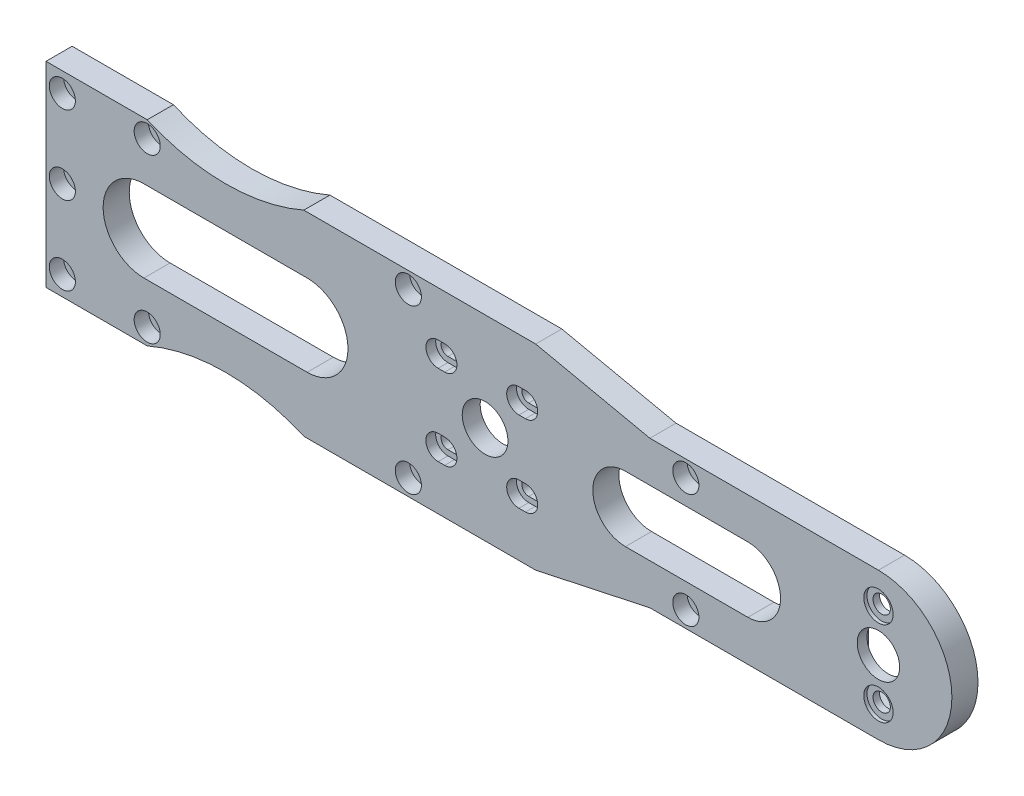
SolidWorks part; units mm, degrees
material "6061 合金"
ref_plane "前视基准面" through (0, 0, 0) normal (0, 0, 1) x (1, 0, 0)
ref_plane "上视基准面" through (0, 0, 0) normal (0, 1, 0) x (1, 0, 0)
ref_plane "右视基准面" through (0, 0, 0) normal (1, 0, 0) x (0, 0, -1)
sketch "草图1" plane through (0, 0, 0) normal (0, 0, 1) x (1, 0, 0)
  line L0 (128.1737, 22.5) -> (58.1737, 22.5)
  line L1 (23.1737, 30) -> (-47.8471, 30)
  line L2 (-96.8263, 0) -> (-46.8263, 0) construction
  line L3 (23.1737, -30) -> (-47.8471, -30)
  line L4 (-126.8263, 30) -> (-126.8263, -30)
  line L5 (-95.8054, -30) -> (-126.8263, -30)
  line L6 (-95.8054, 30) -> (-126.8263, 30)
  line L7 (58.1737, 22.5) -> (23.1737, 30)
  line L8 (-96.8263, 12.5) -> (-46.8263, 12.5)
  line L9 (23.1737, -30) -> (58.1737, -22.5)
  line L10 (58.1737, -22.5) -> (128.1737, -22.5)
  line L11 (-96.8263, -12.5) -> (-46.8263, -12.5)
  arc A0 (128.1737, -22.5) -> (128.1737, 22.5) centre (128.1737, 0) ccw
  arc A1 (-96.8263, 12.5) -> (-96.8263, -12.5) centre (-96.8263, 0) ccw
  arc A2 (-46.8263, -12.5) -> (-46.8263, 12.5) centre (-46.8263, 0) ccw
  arc A3 (-95.8054, 30) -> (-47.8471, 30) centre (-71.8263, 85) ccw
  arc A4 (-47.8471, -30) -> (-95.8054, -30) centre (-71.8263, -85) ccw
  point P15 (-71.8263, 0)
  dimension "D3" = 45
  dimension "D7" = 12.5
  dimension "D11" = 55
  dimension "D12" = 120
  dimension "D13" = 55
  dimension "D1" = 60
  dimension "D2" = 255
  dimension "D4" = 70
  dimension "D5" = 30
  dimension "D6" = 70
  dimension "D8" = 50
  dimension "D9" = 30
  dimension "D10" = 150
extrude "凸台-拉伸1" add sketch "草图1" along normal blind 8
sketch "草图2" plane through (0, 0, 8) normal (0, 0, 1) x (1, 0, 0)
  line L0 (50.6737, 0) -> (88.1737, 0) construction
  line L1 (50.6737, 10) -> (88.1737, 10)
  line L2 (50.6737, -10) -> (88.1737, -10)
  arc A0 (50.6737, 10) -> (50.6737, -10) centre (50.6737, 0) ccw
  arc A1 (88.1737, -10) -> (88.1737, 10) centre (88.1737, 0) ccw
  point P3 (69.4237, 0)
  dimension "D1" = 40
  dimension "D3" = 10
  dimension "D2" = 37.5
extrude "切除-拉伸1" cut sketch "草图2" against normal blind 10
hole_wizard "M4 六角凹头螺钉的柱形沉头孔1" positions "草图4" profile "草图3" counterbore size "M4" standard "Iso" end condition through all
sketch "草图4" plane through (0, 0, 8) normal (0, 0, 1) x (1, 0, 0)
  line L0 (-126.8263, 30) -> (-126.8263, -30) construction
  arc A0 (-96.8263, 12.5) -> (-96.8263, -12.5) centre (-96.8263, 0) ccw construction
  point P0 (-121.8263, 0)
  point P2 (-121.8263, -24)
  point P4 (-121.8263, 24)
  point P6 (-95.8263, 25)
  point P8 (-95.8263, -25)
  point P10 (-15.8263, -25)
  point P12 (-15.8263, 25)
  point P18 (-109.3263, 0)
  point P38 (69.1737, 17.5)
  point P40 (69.1737, -17.5)
  dimension "D1" = 5
  dimension "D2" = 24
  dimension "D3" = 24
  dimension "D4" = 0
  dimension "D5" = 26
  dimension "D6" = 80
  dimension "D7" = 50
  dimension "D8" = 25
  dimension "D9" = 85
  dimension "D10" = 35
  dimension "D11" = 17.5
sketch "草图3" plane through (-121.8263, 0, 8) normal (1, 0, 0) x (0, -1, 0)
  line L0 (0, 0) -> (0, 8)
  line L1 (0, 8) -> (2.25, 8)
  line L3 (2.25, 8) -> (2.25, 4.4)
  line L4 (2.25, 4.4) -> (4, 4.4)
  line L5 (4, 4.4) -> (4, 0)
  line L7 (4, 0) -> (0, 0)
  line L11 (0, -6.35) -> (0, 107.95) construction
  dimension "通孔孔直径" = 4.5
  dimension "通孔孔深度" = 8
  dimension "柱形沉头孔直径" = 8
  dimension "柱形沉头孔深度" = 4.4
sketch "草图11" plane through (0, 0, 0) normal (0, 0, -1) x (-1, 0, 0)
  line L9 (-88.1737, -13) -> (-50.6737, -13)
  line L10 (-50.6737, 13) -> (-88.1737, 13)
  line L11 (96.423, -27) -> (123.8263, -27)
  line L12 (-88.1737, 20.25) -> (-115.4771, 20.25)
  line L14 (123.8263, 27) -> (96.423, 27)
  line L29 (123.8263, -27) -> (123.8263, 27)
  line L30 (47.2295, 27) -> (-22.8559, 27)
  line L31 (-22.8559, 27) -> (-57.8559, 19.5)
  line L32 (-57.8559, 19.5) -> (-128.1737, 19.5)
  line L38 (-128.1737, -19.5) -> (-57.8559, -19.5)
  line L39 (-57.8559, -19.5) -> (-22.8559, -27)
  line L40 (-22.8559, -27) -> (47.2295, -27)
  line L41 (101.8263, -27) -> (101.8263, -25)
  line L42 (114.8263, 27) -> (101.8263, 27)
  line L45 (-115.2449, -19.5) -> (-88.1737, -19.5)
  line L55 (-100.6534, 3.6412) -> (-112.4771, 3.6412)
  line L60 (96.8263, 15.5) -> (46.8263, 15.5)
  line L61 (46.8263, -15.5) -> (96.8263, -15.5)
  line L62 (96.8263, 15.5) -> (46.8263, 15.5)
  line L63 (46.8263, -15.5) -> (96.8263, -15.5)
  line L65 (-88.1737, 13) -> (-88.1737, 20.25)
  line L66 (-88.1737, -13) -> (-88.1737, -19.5)
  line L70 (101.8263, 27) -> (101.8263, 25)
  line L71 (114.8263, 30) -> (114.8263, -30)
  line L72 (114.8263, 27) -> (114.8263, -27)
  line L74 (47.2295, 27) -> (24.8263, 27)
  line L78 (101.8263, -27) -> (114.8263, -27)
  line L80 (24.8263, 27) -> (24.8263, -27)
  line L82 (24.8263, -27) -> (47.2295, -27)
  line L83 (-115.4771, 20.25) -> (-115.4771, 9.9216)
  line L86 (-112.2449, -4.3588) -> (-100.4212, -4.3588)
  line L87 (-115.2449, -10.2748) -> (-115.2449, -19.5)
  arc A3 (47.2295, 27) -> (96.423, 27) centre (71.8263, 85) ccw
  arc A4 (47.2295, 27) -> (89.8377, 24.6296) centre (71.8263, 85) ccw
  arc A5 (96.423, -27) -> (47.2295, -27) centre (71.8263, -85) ccw
  arc A6 (89.8377, -24.6296) -> (47.2295, -27) centre (71.8263, -85) ccw
  arc A9 (-128.1737, 19.5) -> (-128.1737, -19.5) centre (-128.1737, 0) ccw
  arc A16 (-50.6737, -13) -> (-50.6737, 13) centre (-50.6737, 0) ccw
  arc A17 (-88.1737, 13) -> (-88.1737, -13) centre (-88.1737, 0) ccw
  arc A18 (101.8263, -25) -> (89.8377, -24.6296) centre (95.8263, -25) ccw
  arc A19 (-88.1737, 13) -> (-100.6534, 3.6412) centre (-88.1737, 0) ccw
  arc A43 (-112.4771, 3.6412) -> (-115.4771, 9.9216) centre (-128.1737, 0) ccw
  arc A47 (-100.4212, -4.3588) -> (-88.1737, -13) centre (-88.1737, 0) ccw
  arc A49 (96.8263, -15.5) -> (96.8263, 15.5) centre (96.8263, 0) ccw
  arc A50 (46.8263, 15.5) -> (46.8263, -15.5) centre (46.8263, 0) ccw
  arc A51 (96.8263, -15.5) -> (96.8263, 15.5) centre (96.8263, 0) ccw
  arc A52 (46.8263, 15.5) -> (46.8263, -15.5) centre (46.8263, 0) ccw
  arc A53 (-115.2449, -10.2748) -> (-112.2449, -4.3588) centre (-128.1737, 0) ccw
  arc A58 (89.8377, 24.6296) -> (101.8263, 25) centre (95.8263, 25) ccw
  dimension "D2" = 3
  dimension "D9" = 6
  dimension "D6" = 3
  dimension "D7" = 8
  dimension "D8" = 3
  dimension "D3" = 90
  dimension "D1" = 3
  dimension "D4" = 3
  dimension "D5" = 12
extrude "切除-拉伸2" cut sketch "草图11" against normal blind 4
fillet "圆角2" radius 1.5 20 edges at (-24.8263, -27, 2) (-101.8263, -27, 2) (-114.8263, -27, 2) (-114.8263, 27, 2) (-101.8263, 27, 2) (-24.8263, 27, 2) (88.1737, -19.5, 2) (88.1737, 13, 2) (88.1737, 20.25, 2) (115.4771, 9.9216, 2) (115.4771, 20.25, 2) (100.6534, 3.6412, 2) (112.4771, 3.6412, 2) (115.2449, -19.5, 2) (115.2449, -10.2748, 2) (112.2449, -4.3588, 2) (100.4212, -4.3588, 2) (88.1737, -13, 2) (-89.8377, -24.6296, 2) (-89.8377, 24.6296, 2)
hole_wizard "Ø13.0 (13) 直径孔1" positions "草图13" profile "草图12" hole size "Ø13.0" standard "Gb"
sketch "草图13" plane through (0, 0, 8) normal (0, 0, 1) x (1, 0, 0)
  arc A0 (128.1737, -22.5) -> (128.1737, 22.5) centre (128.1737, 0) ccw construction
  point P0 (128.1737, 0)
  dimension "D1" = 0
sketch "草图12" plane through (128.1737, 0, 8) normal (1, 0, 0) x (0, -1, 0)
  line L0 (0, 0) -> (0, 15.9056)
  line L1 (0, 15.9056) -> (6.5, 12)
  line L2 (6.5, 12) -> (6.5, 0)
  line L5 (6.5, 0) -> (0, 0)
  line L10 (0, 15.9056) -> (-6.5, 12) construction
  line L11 (0, -6.35) -> (0, 107.95) construction
  dimension "孔直径" = 13
  dimension "孔深度" = 12
  dimension "导头角度" = 118
sketch "草图14" plane through (0, 0, 0) normal (0, 0, -1) x (-1, 0, 0)
  line L2 (-139.1737, 14.2478) -> (-139.1737, -14.2478)
  line L4 (-117.1737, 14.2478) -> (-117.1737, -14.2478)
  line L5 (-139.1737, 14.2478) -> (-117.1737, -14.2478) construction
  line L6 (-139.1737, -14.2478) -> (-117.1737, 14.2478) construction
  arc A0 (-117.1737, 14.2478) -> (-139.1737, 14.2478) centre (-128.1737, 0) ccw
  arc A1 (-139.1737, -14.2478) -> (-117.1737, -14.2478) centre (-128.1737, 0) ccw
  point P0 (-128.1737, 0)
  dimension "D2" = 18
  dimension "D1" = 22
extrude "切除-拉伸3" cut sketch "草图14" against normal blind 5
hole_wizard "Ø5.3 (5.3) 直径孔1" positions "草图16" profile "草图15" hole size "Ø5.3" standard "Gb"
sketch "草图16" plane through (0, 0, 8) normal (0, 0, 1) x (1, 0, 0)
  circle A1 centre (128.1737, 0) radius 6.5 construction
  point P0 (128.1737, 13)
  point P2 (128.1737, -13)
  dimension "D2" = 0
  dimension "D1" = 26
  dimension "D3" = 13
sketch "草图15" plane through (128.1737, 13, 8) normal (1, 0, 0) x (0, -1, 0)
  line L0 (0, 0) -> (0, 13.5923)
  line L1 (0, 13.5923) -> (2.65, 12)
  line L2 (2.65, 12) -> (2.65, 0)
  line L5 (2.65, 0) -> (0, 0)
  line L10 (0, 13.5923) -> (-2.65, 12) construction
  line L11 (0, -6.35) -> (0, 107.95) construction
  dimension "孔直径" = 5.3
  dimension "孔深度" = 12
  dimension "导头角度" = 118
hole_wizard "Ø10.0 (10) 直径孔1" positions "草图18" profile "草图17" hole size "Ø10.0" standard "Gb"
sketch "草图18" plane through (0, 0, 0) normal (0, 0, -1) x (-1, 0, 0)
  line L0 (126.8263, 30) -> (126.8263, -30) construction
  point P0 (-7.6737, 0)
  dimension "D1" = 134.5
sketch "草图17" plane through (7.6737, 0, 0) normal (1, 0, 0) x (0, 1, 0)
  line L0 (0, 0) -> (0, 16.206)
  line L1 (0, 16.206) -> (7, 12)
  line L2 (7, 12) -> (7, 0)
  line L5 (7, 0) -> (0, 0)
  line L10 (0, 16.206) -> (-7, 12) construction
  line L11 (0, -6.35) -> (0, 107.95) construction
  dimension "孔直径" = 14
  dimension "孔深度" = 12
  dimension "导头角度" = 118
sketch "草图21" plane through (0, 0, 0) normal (0, 0, -1) x (-1, 0, 0)
  circle A0 centre (-7.6737, 0) radius 13.5
  dimension "D1" = 27
extrude "切除-拉伸4" cut sketch "草图21" against normal blind 2.5
sketch "草图22" plane through (0, 0, 8) normal (0, 0, 1) x (1, 0, 0)
  circle A0 centre (128.1737, -13) radius 4.5
  circle A1 centre (128.1737, 13) radius 4.5
extrude "切除-拉伸5" cut sketch "草图22" against normal blind 1
sketch "草图23" plane through (0, 0, 8) normal (0, 0, 1) x (1, 0, 0)
  line L0 (20.0481, 12.3744) -> (18.0481, 12.3744) construction
  line L1 (-4.7006, 12.3744) -> (20.0481, 12.3744) construction
  line L2 (-4.7006, 12.3744) -> (-4.7006, -12.3744) construction
  line L3 (-4.7006, -12.3744) -> (20.0481, -12.3744) construction
  line L4 (20.0481, 12.3744) -> (20.0481, -12.3744) construction
  line L5 (-4.7006, 12.3744) -> (20.0481, -12.3744) construction
  line L6 (-4.7006, -12.3744) -> (20.0481, 12.3744) construction
  line L7 (20.0481, 10.2744) -> (18.0481, 10.2744)
  line L8 (20.0481, 14.4744) -> (18.0481, 14.4744)
  line L9 (-6.7006, 12.3744) -> (-4.7006, 12.3744) construction
  line L10 (-6.7006, 14.4744) -> (-4.7006, 14.4744)
  line L11 (-6.7006, 10.2744) -> (-4.7006, 10.2744)
  line L12 (20.0481, -12.3744) -> (18.0481, -12.3744) construction
  line L13 (20.0481, -14.4744) -> (18.0481, -14.4744)
  line L14 (20.0481, -10.2744) -> (18.0481, -10.2744)
  line L15 (-4.7006, -12.3744) -> (-6.7006, -12.3744) construction
  line L16 (-4.7006, -14.4744) -> (-6.7006, -14.4744)
  line L17 (-4.7006, -10.2744) -> (-6.7006, -10.2744)
  arc A0 (20.0481, 10.2744) -> (20.0481, 14.4744) centre (20.0481, 12.3744) ccw
  arc A1 (18.0481, 14.4744) -> (18.0481, 10.2744) centre (18.0481, 12.3744) ccw
  arc A2 (-6.7006, 14.4744) -> (-6.7006, 10.2744) centre (-6.7006, 12.3744) ccw
  arc A3 (-4.7006, 10.2744) -> (-4.7006, 14.4744) centre (-4.7006, 12.3744) ccw
  arc A4 (20.0481, -14.4744) -> (20.0481, -10.2744) centre (20.0481, -12.3744) ccw
  arc A5 (18.0481, -10.2744) -> (18.0481, -14.4744) centre (18.0481, -12.3744) ccw
  arc A6 (-4.7006, -14.4744) -> (-4.7006, -10.2744) centre (-4.7006, -12.3744) ccw
  arc A7 (-6.7006, -10.2744) -> (-6.7006, -14.4744) centre (-6.7006, -12.3744) ccw
  point P0 (7.6737, 0)
  point P6 (19.0481, 12.3744)
  point P12 (-5.7006, 12.3744)
  point P18 (19.0481, -12.3744)
  point P24 (-5.7006, -12.3744)
  dimension "D1" = 4.2
  dimension "D2" = 35
  dimension "D3" = 4.2
  dimension "D4" = 4.2
  dimension "D5" = 4.2
  dimension "D6" = 2
  dimension "D7" = 2
  dimension "D8" = 2
  dimension "D9" = 2
extrude "切除-拉伸6" cut sketch "草图23" against normal through all
sketch "草图24" plane through (0, 0, 8) normal (0, 0, 1) x (1, 0, 0)
  line L0 (-4.7006, 12.3744) -> (-6.7006, 12.3744) construction
  line L1 (-4.7006, 8.6244) -> (-6.7006, 8.6244)
  line L2 (-4.7006, 16.1244) -> (-6.7006, 16.1244)
  line L3 (18.0481, 12.3744) -> (20.0481, 12.3744) construction
  line L4 (18.0481, 16.1244) -> (20.0481, 16.1244)
  line L5 (18.0481, 8.6244) -> (20.0481, 8.6244)
  line L6 (18.0481, -12.3744) -> (20.0481, -12.3744) construction
  line L7 (18.0481, -8.6244) -> (20.0481, -8.6244)
  line L8 (18.0481, -16.1244) -> (20.0481, -16.1244)
  line L9 (-4.7006, -12.3744) -> (-6.7006, -12.3744) construction
  line L10 (-4.7006, -16.1244) -> (-6.7006, -16.1244)
  line L11 (-4.7006, -8.6244) -> (-6.7006, -8.6244)
  arc A0 (-4.7006, 8.6244) -> (-4.7006, 16.1244) centre (-4.7006, 12.3744) ccw
  arc A1 (-6.7006, 16.1244) -> (-6.7006, 8.6244) centre (-6.7006, 12.3744) ccw
  arc A2 (18.0481, 16.1244) -> (18.0481, 8.6244) centre (18.0481, 12.3744) ccw
  arc A3 (20.0481, 8.6244) -> (20.0481, 16.1244) centre (20.0481, 12.3744) ccw
  arc A4 (18.0481, -8.6244) -> (18.0481, -16.1244) centre (18.0481, -12.3744) ccw
  arc A5 (20.0481, -16.1244) -> (20.0481, -8.6244) centre (20.0481, -12.3744) ccw
  arc A6 (-4.7006, -16.1244) -> (-4.7006, -8.6244) centre (-4.7006, -12.3744) ccw
  arc A7 (-6.7006, -8.6244) -> (-6.7006, -16.1244) centre (-6.7006, -12.3744) ccw
  point P4 (-5.7006, 12.3744)
  point P9 (19.0481, 12.3744)
  point P18 (19.0481, -12.3744)
  point P27 (-5.7006, -12.3744)
  dimension "D1" = 7.5
  dimension "D2" = 7.5
  dimension "D3" = 7.5
  dimension "D4" = 7.5
extrude "切除-拉伸7" cut sketch "草图24" against normal blind 3
fillet "圆角3" radius 1.5 6 edges at (117.1737, -14.2478, 2.5) (139.1737, -14.2478, 2.5) (139.1737, 14.2478, 2.5) (117.1737, 14.2478, 2.5) (-47.2295, 27, 2) (-47.2295, -27, 2)
